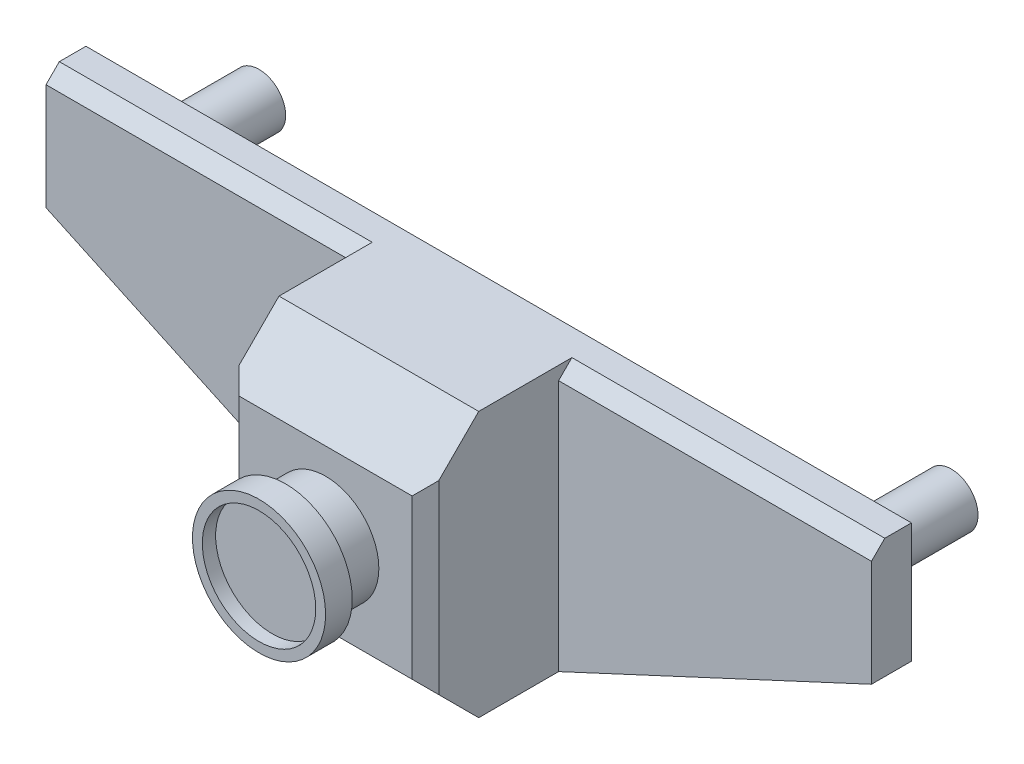
SolidWorks part; units mm, degrees
ref_plane "Alzado" through (0, 0, 0) normal (0, 0, 1) x (1, 0, 0)
ref_plane "Planta" through (0, 0, 0) normal (0, 1, 0) x (1, 0, 0)
ref_plane "Vista lateral" through (0, 0, 0) normal (1, 0, 0) x (0, 0, -1)
sketch "Croquis1" plane through (0, 0, 0) normal (0, 0, 1) x (1, 0, 0)
  line L0 (-15.5108, -3.2963) -> (7.9892, -14.2222)
  line L1 (-15.5108, 5.7037) -> (46.4892, 5.7037)
  line L2 (-15.5108, 5.7037) -> (-15.5108, -3.2963)
  line L4 (46.4892, 5.7037) -> (46.4892, -3.2963)
  line L5 (7.9892, -14.2222) -> (22.9892, -14.2222)
  line L6 (22.9892, -14.2222) -> (46.4892, -3.2963)
  point P8 (0, 0)
  dimension "D7" = 9
  dimension "D8" = 15
  dimension "D9" = 23.5
extrude "Saliente-Extruir2" add sketch "Croquis1" along normal blind 3
sketch "Croquis2" plane through (0, 0, 0) normal (0, 0, -1) x (-1, 0, 0)
  line L0 (-46.4892, 5.7037) -> (15.5108, 5.7037) construction
  line L1 (-46.4892, -3.2963) -> (-46.4892, 5.7037) construction
  circle A0 centre (-41.4892, 0.7037) radius 2
  circle A1 centre (10.5108, 0.7037) radius 2
  point P6 (0, 0)
  dimension "D2" = 5
  dimension "D3" = 4
  dimension "D4" = 4
  dimension "D5" = 5
  dimension "D1" = 52
extrude "Saliente-Extruir3" add sketch "Croquis2" along normal blind 8
sketch "Croquis3" plane through (0, 0, 3) normal (0, 0, 1) x (1, 0, 0)
  line L0 (46.4892, 5.7037) -> (-15.5108, 5.7037) construction
  line L1 (7.9892, -14.2222) -> (22.9892, -14.2222)
  line L2 (7.9892, -14.2222) -> (7.9892, 5.7037)
  line L3 (7.9892, 5.7037) -> (22.9892, 5.7037)
  line L4 (22.9892, -14.2222) -> (22.9892, 5.7037)
extrude "Saliente-Extruir4" add sketch "Croquis3" along normal blind 10
chamfer "Chaflán1" distance 4 angle 45 2 edges at (15.4892, -14.2222, 13) (15.4892, 5.7037, 13)
chamfer "Chaflán2" distance 1 angle 45 2 edges at (22.9892, -4.2593, 13) (7.9892, -4.2593, 13)
sketch "Croquis4" plane through (0, 0, 13) normal (0, 0, 1) x (1, 0, 0)
  line L0 (8.9892, -4.2593) -> (21.9892, -4.2593) construction
  line L1 (8.9892, 1.7037) -> (8.9892, -10.2222) construction
  line L2 (21.9892, -10.2222) -> (21.9892, 1.7037) construction
  circle A0 centre (15.4892, -4.2593) radius 4
  point P8 (15.4892, -4.2593)
  dimension "D1" = 8
extrude "Saliente-Extruir5" add sketch "Croquis4" along normal blind 3 contours A0
sketch "Croquis5" plane through (0, 0, 16) normal (0, 0, 1) x (1, 0, 0)
  circle A0 centre (15.4892, -4.2593) radius 5
  dimension "D1" = 10
extrude "Saliente-Extruir6" add sketch "Croquis5" along normal blind 2
sketch "Croquis6" plane through (0, 0, 18) normal (0, 0, 1) x (1, 0, 0)
  circle A0 centre (15.4892, -4.2593) radius 4.2593
extrude "Cortar-Extruir1" cut sketch "Croquis6" against normal blind 1
chamfer "Chaflán3" distance 1 angle 45 2 edges at (-3.7608, 5.7037, 3) (34.7392, 5.7037, 3)
